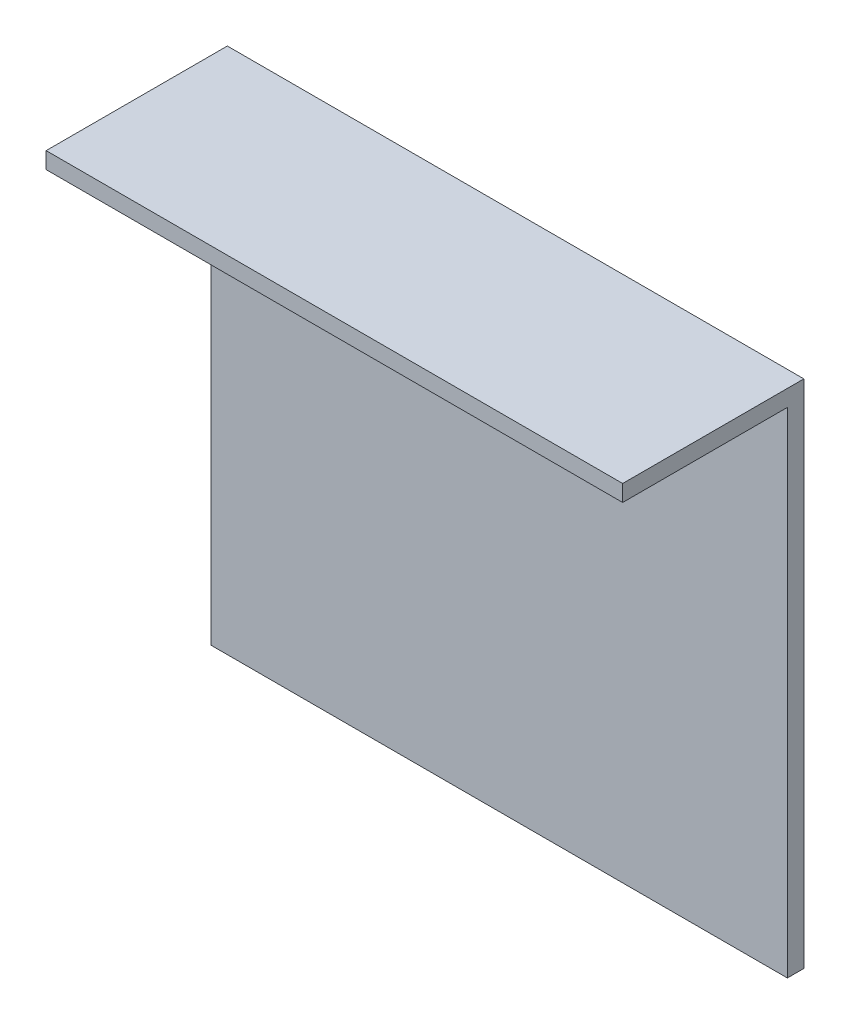
SolidWorks part; units mm, degrees
ref_plane "前视基准面" through (0, 0, 0) normal (0, 0, 1) x (1, 0, 0)
ref_plane "上视基准面" through (0, 0, 0) normal (0, 1, 0) x (1, 0, 0)
ref_plane "右视基准面" through (0, 0, 0) normal (1, 0, 0) x (0, 0, -1)
sketch "草图1" plane through (0, 0, 0) normal (0, 0, 1) x (1, 0, 0)
  line L1 (-35, 31) -> (35, 31)
  line L2 (-35, 31) -> (-35, -31)
  line L3 (-35, -31) -> (35, -31)
  line L4 (35, 31) -> (35, -31)
  line L5 (-35, 31) -> (35, -31) construction
  line L6 (-35, -31) -> (35, 31) construction
  point P0 (0, 0)
  dimension "D1" = 62
  dimension "D2" = 70
extrude "凸台-拉伸1" add sketch "草图1" along normal blind 2
sketch "草图2" plane through (0, 0, 2) normal (0, 0, 1) x (1, 0, 0)
  line L0 (35, -31) -> (35, 31) construction
  line L1 (-35, 31) -> (35, 31)
  line L2 (-35, 31) -> (-35, 29)
  line L3 (-35, 29) -> (35, 29)
  line L4 (35, 31) -> (35, 29)
  dimension "D1" = 2
extrude "凸台-拉伸2" add sketch "草图2" along normal blind 20
